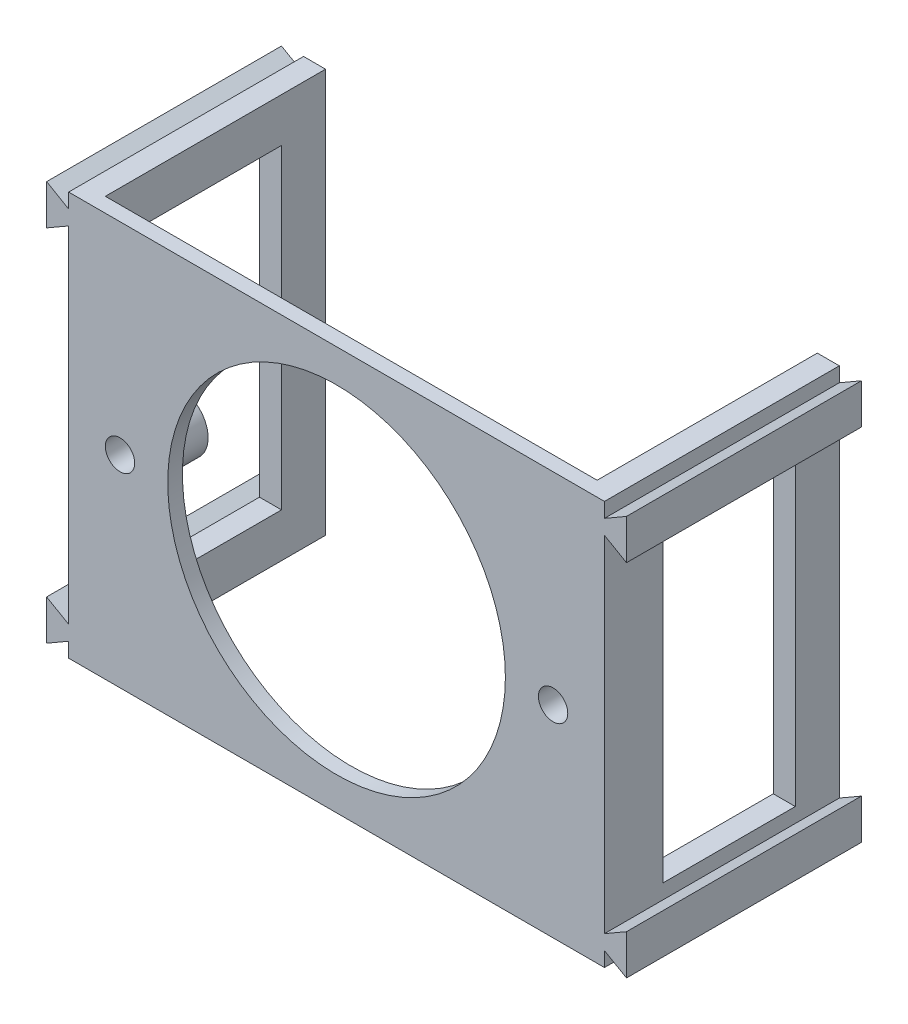
SolidWorks part; units mm, degrees
ref_plane "Front Plane" through (0, 0, 0) normal (0, 0, 1) x (1, 0, 0)
ref_plane "Top Plane" through (0, 0, 0) normal (0, 1, 0) x (1, 0, 0)
ref_plane "Right Plane" through (0, 0, 0) normal (1, 0, 0) x (0, 0, -1)
sketch "Sketch2" plane through (0, 0, 0) normal (0, 0, 1) x (1, 0, 0)
  line L0 (-18.25, 13.75) -> (-18.25, -13.75)
  line L1 (-16.25, 11.75) -> (16.25, 11.75) construction
  line L2 (-16.25, 11.75) -> (-16.25, -11.75) construction
  line L3 (-16.25, -11.75) -> (16.25, -11.75) construction
  line L4 (16.25, 11.75) -> (16.25, -11.75) construction
  line L5 (-16.25, 11.75) -> (16.25, -11.75) construction
  line L6 (-16.25, -11.75) -> (16.25, 11.75) construction
  line L7 (-18.25, -13.75) -> (18.25, -13.75)
  line L8 (18.25, 13.75) -> (18.25, -13.75)
  line L9 (-18.25, 13.75) -> (18.25, 13.75)
  line L10 (-18.25, 0) -> (18.25, 0) construction
  circle A0 centre (0, 0) radius 11.5
  circle A1 centre (-14.75, 0) radius 1
  circle A3 centre (14.75, 0) radius 1
  point P0 (0, 0)
  point P18 (0, 0)
  dimension "D1" = 23
  dimension "D5" = 2
  dimension "D6" = 1.5
  dimension "D2" = 32.5
  dimension "D3" = 23.5
  dimension "D7" = 1.5
  dimension "D4" = 2
extrude "Boss-Extrude1" add sketch "Sketch2" against normal blind 1
sketch "Sketch4" plane through (0, 0, -1) normal (0, 0, -1) x (-1, 0, 0)
  line L0 (-16.75, 13.75) -> (-16.75, 4)
  line L1 (-18.25, 13.75) -> (18.25, 13.75) construction
  line L2 (18.25, -13.75) -> (-18.25, -13.75) construction
  line L3 (-18.25, -13.75) -> (-18.25, 13.75) construction
  line L4 (-16.75, 13.75) -> (-18.25, 13.75)
  line L5 (-18.25, 13.75) -> (-18.25, -13.75)
  line L6 (-18.25, -13.75) -> (-16.75, -13.75)
  line L7 (-16.75, -4) -> (-16.75, -13.75)
  arc A0 (-14.75, -2) -> (-14.75, 2) centre (-14.75, 0) ccw
  arc A1 (-14.75, -2) -> (-16.75, -4) centre (-14.75, -4) ccw
  arc A2 (-16.75, 4) -> (-14.75, 2) centre (-14.75, 4) ccw
  circle A4 centre (-14.75, 0) radius 1 construction
  circle A5 centre (-14.75, 0) radius 1
  point P1 (0, 0)
  dimension "D1" = 1.5
extrude "Boss-Extrude2" add sketch "Sketch4" along normal blind 3 contours A2 A0 A1 L7 L6 L5 L4 L0
sketch "Sketch5" plane through (0, 0, -4) normal (0, 0, -1) x (-1, 0, 0)
  line L1 (-18.25, 13.75) -> (-16.75, 13.75)
  line L2 (-18.25, 13.75) -> (-18.25, -13.75)
  line L3 (-18.25, -13.75) -> (-16.75, -13.75)
  line L4 (-16.75, 13.75) -> (-16.75, -13.75)
extrude "Boss-Extrude3" add sketch "Sketch5" along normal blind 12
sketch "Sketch6" plane through (18.25, 0, 0) normal (1, 0, 0) x (0, 0, -1)
  line L4 (16, -13.75) -> (0, -13.75) construction
  line L5 (16, 13.75) -> (1, 13.75)
  line L6 (16, 13.75) -> (16, -13.75)
  line L7 (16, -13.75) -> (1, -13.75)
  line L8 (1, 13.75) -> (1, -13.75)
  line L10 (4, -4) -> (4, 4) construction
  line L11 (13, 10.75) -> (13, -10.75)
  line L12 (13, -10.75) -> (4, -10.75)
  line L13 (4, 10.75) -> (4, -10.75)
  line L14 (13, 10.75) -> (4, 10.75)
  dimension "D1" = 3
  dimension "D2" = 3
extrude "Cut-Extrude1" cut sketch "Sketch6" against normal up to surface (1.5 mm away) contours L11 L12 L13 L14 up to face at (16.75, 0, -5.5)
sketch "Sketch7" plane through (0, 0, -16) normal (0, 0, -1) x (-1, 0, 0)
  line L0 (-18.25, 12.75) -> (-19.75, 13.616)
  line L1 (-18.25, 13.75) -> (-18.25, -13.75) construction
  line L2 (-19.75, 13.616) -> (-19.75, 10.884)
  line L3 (-19.75, 10.884) -> (-18.25, 11.75)
  line L4 (-18.25, 11.75) -> (-18.25, 12.75)
  line L6 (2.2, 0) -> (-2.2, 0) construction
  line L7 (-19.75, -10.884) -> (-18.25, -11.75)
  line L8 (-19.75, -13.616) -> (-19.75, -10.884)
  line L9 (-18.25, -12.75) -> (-19.75, -13.616)
  line L10 (-18.25, -11.75) -> (-18.25, -12.75)
  point P4 (-20.25, 9.3991)
  dimension "D1" = 60
  dimension "D2" = 1.5
  dimension "D3" = 1
  dimension "D4" = 1
  dimension "D5" = 60
extrude "Boss-Extrude4" add sketch "Sketch7" against normal up to surface (16 mm away) up to face at (15.75, 0, 0)
mirror "Mirror1" about plane through (0, 0, 0) normal (1, 0, 0) of "Boss-Extrude2", "Boss-Extrude4", "Cut-Extrude1", "Boss-Extrude3"
